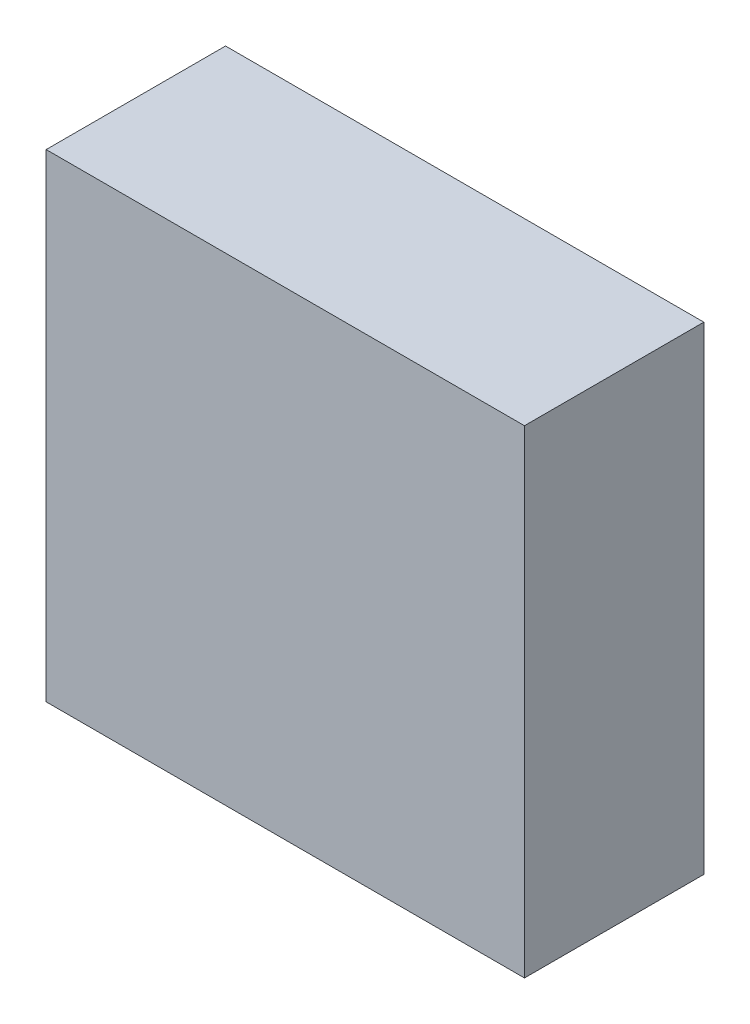
SolidWorks part; units mm, degrees
ref_plane "前视基准面" through (0, 0, 0) normal (0, 0, 1) x (1, 0, 0)
ref_plane "上视基准面" through (0, 0, 0) normal (0, 1, 0) x (1, 0, 0)
ref_plane "右视基准面" through (0, 0, 0) normal (1, 0, 0) x (0, 0, -1)
sketch "草图1" plane through (0, 0, 0) normal (0, 0, 1) x (1, 0, 0)
  line L2 (-3.6052, 4.2411) -> (4.3948, 4.2411)
  line L3 (-3.6052, 4.2411) -> (-3.6052, -3.7589)
  line L4 (-3.6052, -3.7589) -> (4.3948, -3.7589)
  line L5 (4.3948, 4.2411) -> (4.3948, -3.7589)
  dimension "D1" = 8
  dimension "D2" = 8
extrude "凸台-拉伸1" add sketch "草图1" along normal blind 3
